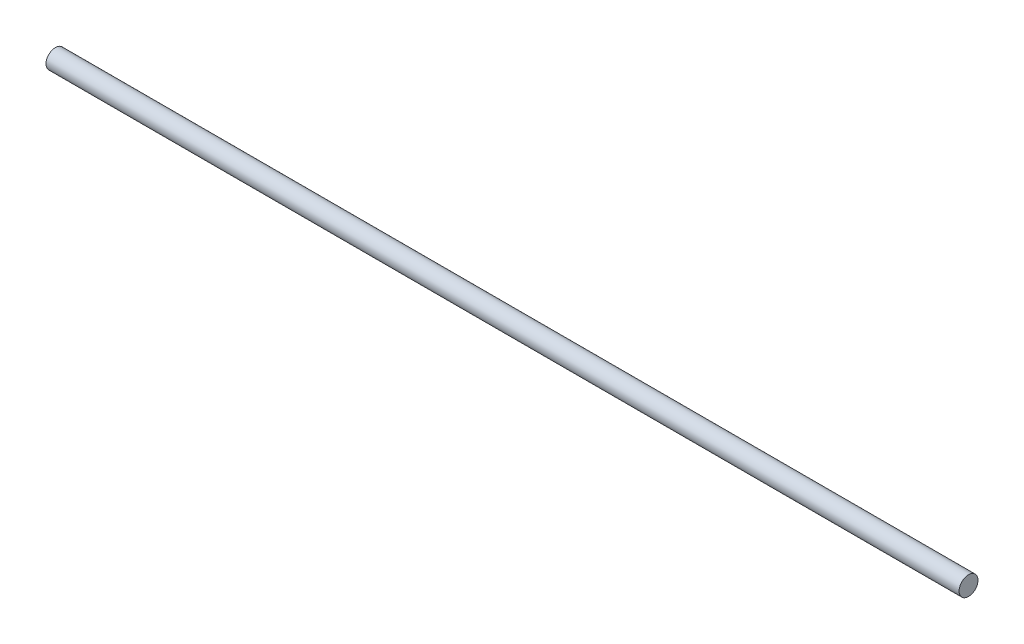
SolidWorks part; units mm, degrees
ref_plane "前视基准面" through (0, 0, 0) normal (0, 0, 1) x (1, 0, 0)
ref_plane "上视基准面" through (0, 0, 0) normal (0, 1, 0) x (1, 0, 0)
ref_plane "右视基准面" through (0, 0, 0) normal (1, 0, 0) x (0, 0, -1)
sketch "草图1" plane through (0, 0, 0) normal (1, 0, 0) x (0, 0, -1)
  circle A0 centre (0, 0) radius 3
  dimension "D1" = 6
extrude "凸台-拉伸1" add sketch "草图1" along normal blind 290
